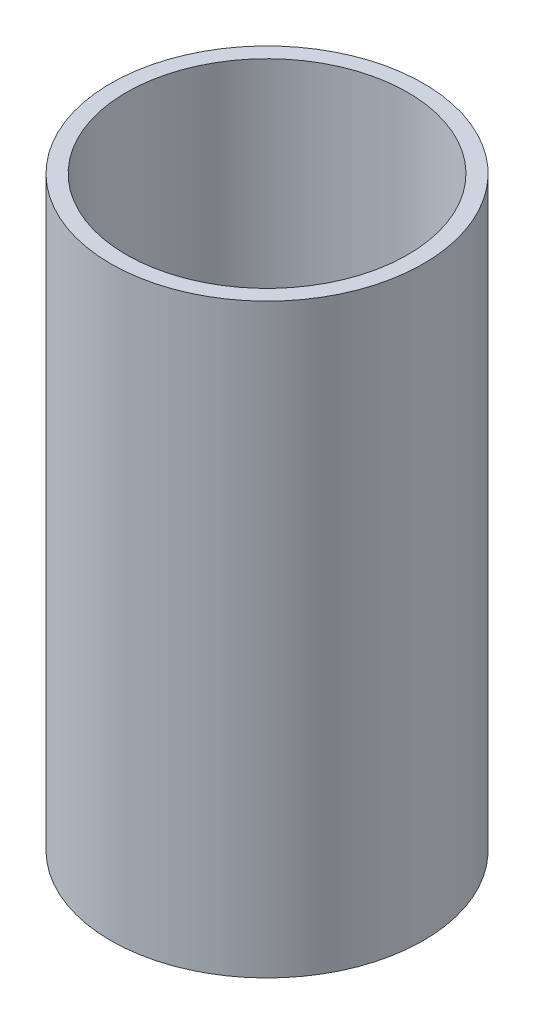
SolidWorks part; units mm, degrees
ref_plane "Front Plane" through (0, 0, 0) normal (0, 0, 1) x (1, 0, 0)
ref_plane "Top Plane" through (0, 0, 0) normal (0, 1, 0) x (1, 0, 0)
ref_plane "Right Plane" through (0, 0, 0) normal (1, 0, 0) x (0, 0, -1)
sketch "Sketch1" plane through (0, 0, 0) normal (0, 1, 0) x (1, 0, 0)
  circle A0 centre (0, 0) radius 36
  circle A1 centre (0, 0) radius 40
  dimension "D1" = 80
  dimension "D2" = 4
extrude "Boss-Extrude1" add sketch "Sketch1" along normal blind 150
